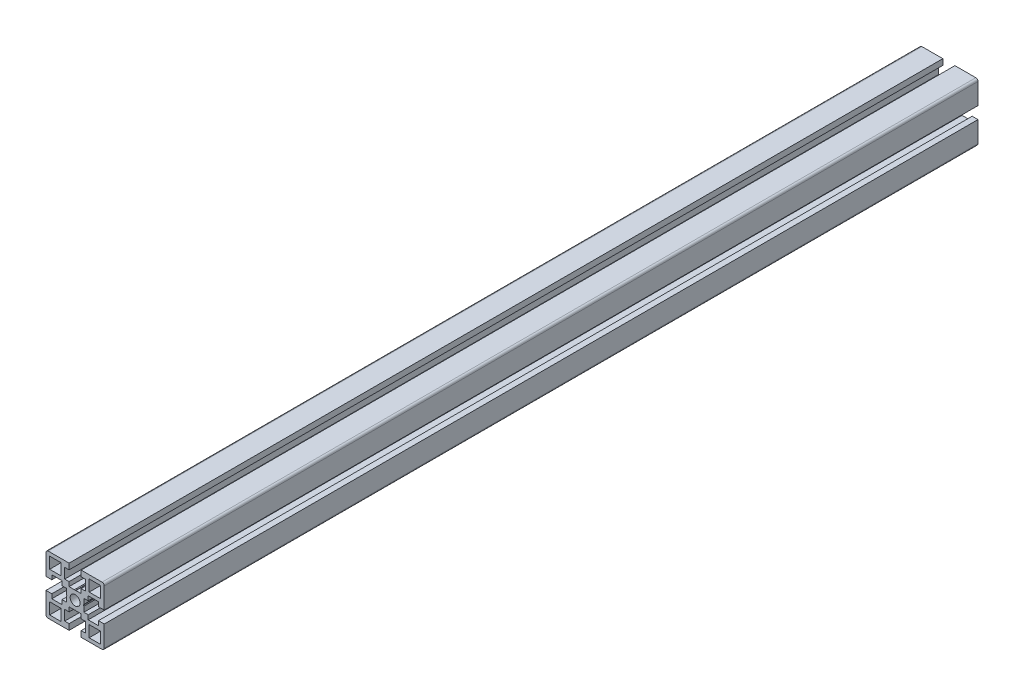
SolidWorks part; units mm, degrees
ref_plane "Front Plane" through (0, 0, 0) normal (0, 0, 1) x (1, 0, 0)
ref_plane "Top Plane" through (0, 0, 0) normal (0, 1, 0) x (1, 0, 0)
ref_plane "Right Plane" through (0, 0, 0) normal (1, 0, 0) x (0, 0, -1)
sketch "Sketch1" plane through (0, 0, 0) normal (0, 0, 1) x (1, 0, 0)
  line L0 (-17.5, 17.5) -> (-9.65, 17.5)
  line L1 (-9.65, 17.5) -> (-9.65, 9.65)
  line L2 (-9.65, 9.65) -> (-17.5, 9.65)
  line L3 (-17.5, 9.65) -> (-17.5, 17.5)
  line L4 (9.65, 17.5) -> (17.5, 17.5)
  line L5 (17.5, 17.5) -> (17.5, 9.65)
  line L6 (17.5, 9.65) -> (9.65, 9.65)
  line L7 (9.65, 9.65) -> (9.65, 17.5)
  line L8 (-9.65, -9.65) -> (-9.65, -17.5)
  line L9 (-9.65, -17.5) -> (-17.5, -17.5)
  line L10 (-17.5, -17.5) -> (-17.5, -9.65)
  line L11 (-17.5, -9.65) -> (-9.65, -9.65)
  line L12 (17.5, -17.5) -> (9.65, -17.5)
  line L13 (9.65, -17.5) -> (9.65, -9.65)
  line L14 (9.65, -9.65) -> (17.5, -9.65)
  line L15 (17.5, -9.65) -> (17.5, -17.5)
  line L16 (-7.15, 16) -> (-4.15, 16)
  line L17 (-4.15, 16) -> (-4.15, 20)
  line L18 (-4.15, 20) -> (-18.5, 20)
  line L19 (-20, 18.5) -> (-20, 4.15)
  line L20 (-20, 4.15) -> (-16, 4.15)
  line L21 (-16, 4.15) -> (-16, 7.15)
  line L22 (-16, 7.15) -> (-9, 7.15)
  line L23 (-9, 7.15) -> (-9, 4.15)
  line L24 (-9, 4.15) -> (-6, 4.15)
  line L25 (-6, 4.15) -> (-6, 0.5196)
  line L26 (-6, 0.5196) -> (-5.7, 0)
  line L27 (-5.7, 0) -> (-6, -0.5196)
  line L28 (-6, -0.5196) -> (-6, -4.15)
  line L29 (-6, -4.15) -> (-9, -4.15)
  line L30 (-9, -4.15) -> (-9, -7.15)
  line L31 (-9, -7.15) -> (-16, -7.15)
  line L32 (-16, -7.15) -> (-16, -4.15)
  line L33 (-16, -4.15) -> (-20, -4.15)
  line L34 (-20, -4.15) -> (-20, -18.5)
  line L35 (-18.5, -20) -> (-4.15, -20)
  line L36 (-4.15, -20) -> (-4.15, -16)
  line L37 (-4.15, -16) -> (-7.15, -16)
  line L38 (-7.15, -16) -> (-7.15, -9)
  line L39 (-7.15, -9) -> (-4.15, -9)
  line L40 (-4.15, -9) -> (-4.15, -6)
  line L41 (-4.15, -6) -> (-0.5196, -6)
  line L42 (-0.5196, -6) -> (0, -5.7)
  line L43 (0, -5.7) -> (0.5196, -6)
  line L44 (0.5196, -6) -> (4.15, -6)
  line L45 (4.15, -6) -> (4.15, -9)
  line L46 (4.15, -9) -> (7.15, -9)
  line L47 (7.15, -9) -> (7.15, -16)
  line L48 (7.15, -16) -> (4.15, -16)
  line L49 (4.15, -16) -> (4.15, -20)
  line L50 (4.15, -20) -> (18.5, -20)
  line L51 (20, -18.5) -> (20, -4.15)
  line L52 (20, -4.15) -> (16, -4.15)
  line L53 (16, -4.15) -> (16, -7.15)
  line L54 (16, -7.15) -> (9, -7.15)
  line L55 (9, -7.15) -> (9, -4.15)
  line L56 (9, -4.15) -> (6, -4.15)
  line L57 (6, -4.15) -> (6, -0.5196)
  line L58 (6, -0.5196) -> (5.7, 0)
  line L59 (5.7, 0) -> (6, 0.5196)
  line L60 (6, 0.5196) -> (6, 4.15)
  line L61 (6, 4.15) -> (9, 4.15)
  line L62 (9, 4.15) -> (9, 7.15)
  line L63 (9, 7.15) -> (16, 7.15)
  line L64 (16, 7.15) -> (16, 4.15)
  line L65 (16, 4.15) -> (20, 4.15)
  line L66 (20, 4.15) -> (20, 18.5)
  line L67 (18.5, 20) -> (4.15, 20)
  line L68 (4.15, 20) -> (4.15, 16)
  line L69 (4.15, 16) -> (7.15, 16)
  line L70 (7.15, 16) -> (7.15, 9)
  line L71 (7.15, 9) -> (4.15, 9)
  line L72 (4.15, 9) -> (4.15, 6)
  line L73 (4.15, 6) -> (0.5196, 6)
  line L74 (0.5196, 6) -> (0, 5.7)
  line L75 (0, 5.7) -> (-0.5196, 6)
  line L76 (-0.5196, 6) -> (-4.15, 6)
  line L77 (-4.15, 6) -> (-4.15, 9)
  line L78 (-4.15, 9) -> (-7.15, 9)
  line L79 (-7.15, 9) -> (-7.15, 16)
  circle A0 centre (0, 0) radius 3.4
  arc A1 (-18.5, 20) -> (-20, 18.5) centre (-18.5, 18.5) ccw
  arc A2 (-20, -18.5) -> (-18.5, -20) centre (-18.5, -18.5) ccw
  arc A3 (18.5, -20) -> (20, -18.5) centre (18.5, -18.5) ccw
  arc A4 (20, 18.5) -> (18.5, 20) centre (18.5, 18.5) ccw
extrude "Boss-Extrude1" add sketch "Sketch1" against normal blind 600
sketch "Sketch2" plane through (0, 20, 0) normal (0, 1, 0) x (1, 0, 0)
  line L0 (0, 600) -> (0, 0) construction
  line L1 (0.5196, 600) -> (0.5196, 0) construction
  line L2 (-49.4804, 300) -> (50.5196, 300)
  line L3 (-49.4804, 300) -> (-49.4804, 400)
  line L4 (-49.4804, 400) -> (50.5196, 400)
  line L5 (50.5196, 300) -> (50.5196, 400)
  line L6 (-49.4804, 300) -> (50.5196, 400) construction
  line L7 (-49.4804, 400) -> (50.5196, 300) construction
  line L8 (0.5196, 350) -> (0, 50)
  line L9 (-50, 0) -> (50, 0)
  line L10 (-50, 0) -> (-50, 100)
  line L11 (-50, 100) -> (50, 100)
  line L12 (50, 0) -> (50, 100)
  line L13 (-50, 0) -> (50, 100) construction
  line L14 (-50, 100) -> (50, 0) construction
  point P4 (0.5196, 350)
  point P12 (0, 50)
  dimension "D1" = 100
  dimension "D2" = 100
  dimension "D3" = 100
  dimension "D4" = 100
  dimension "D5" = 300
  dimension "D6" = 200
